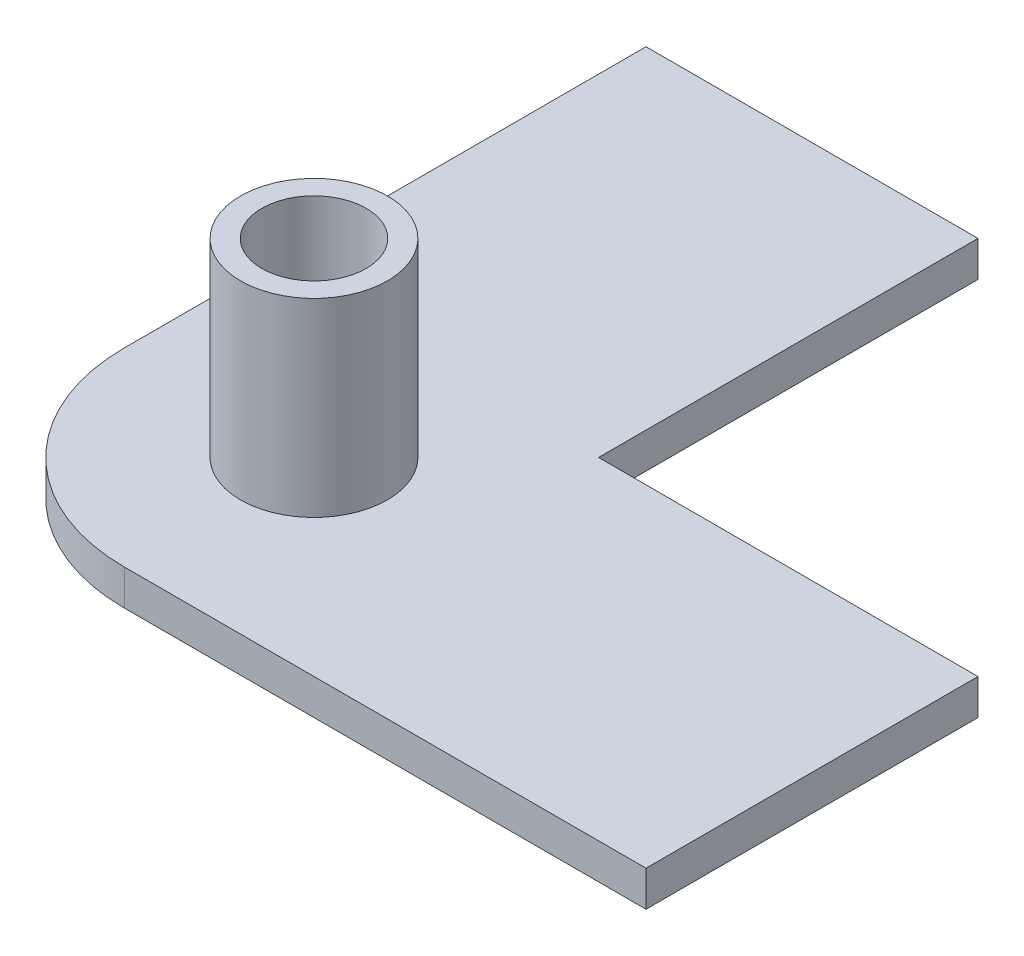
SolidWorks part; units mm, degrees
ref_plane "Front Plane" through (0, 0, 0) normal (0, 0, 1) x (1, 0, 0)
ref_plane "Top Plane" through (0, 0, 0) normal (0, 1, 0) x (1, 0, 0)
ref_plane "Right Plane" through (0, 0, 0) normal (1, 0, 0) x (0, 0, -1)
sketch "Sketch1" plane through (0, 0, 0) normal (0, 1, 0) x (1, 0, 0)
  line L0 (0, 0) -> (0, 11)
  line L1 (0, 0) -> (11, 0)
  line L2 (11, 0) -> (11, 3)
  line L3 (0, 11) -> (3, 11)
  line L4 (-3.9997, 0) -> (-3.9997, 11)
  line L5 (-3.9997, 11) -> (0, 11)
  line L6 (0, -3.9997) -> (11, -3.9997)
  line L7 (11, -3.9997) -> (11, 0)
  line L8 (3, 11) -> (3, 3)
  line L9 (3, 3) -> (11, 3)
  circle A0 centre (0, 0) radius 1.1
  arc A1 (0, -3.9997) -> (-3.9997, 0) centre (0, 0) cw
extrude "Boss-Extrude1" add sketch "Sketch1" along normal blind 0.75 contours A0 L1 L2 L9 L8 L3 L0 | A1 L6 L7 L1 A0 L0 L5 L4
sketch "Sketch2" plane through (0, 0.75, 0) normal (0, 1, 0) x (1, 0, 0)
  circle A0 centre (0, 0) radius 1.1
  circle A1 centre (0, 0) radius 1.55
extrude "Boss-Extrude2" add sketch "Sketch2" along normal blind 4
